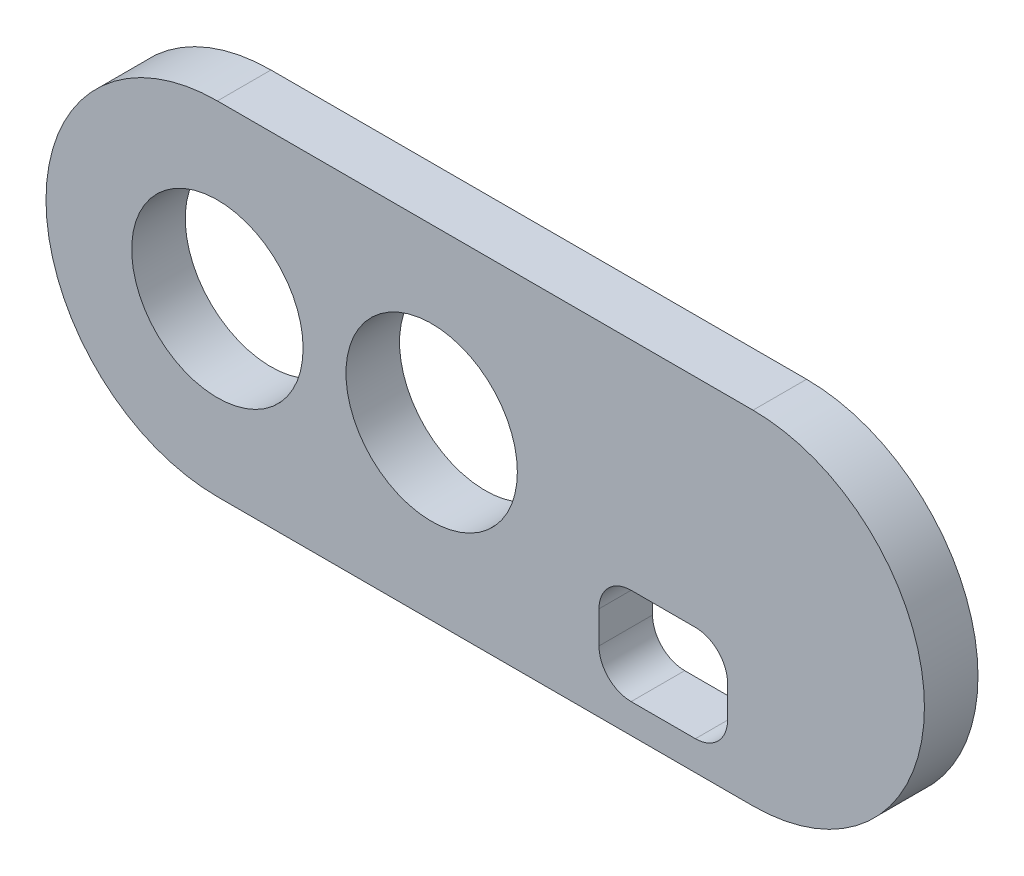
SolidWorks part; units mm, degrees
ref_plane "前视基准面" through (0, 0, 0) normal (0, 0, 1) x (1, 0, 0)
ref_plane "上视基准面" through (0, 0, 0) normal (0, 1, 0) x (1, 0, 0)
ref_plane "右视基准面" through (0, 0, 0) normal (1, 0, 0) x (0, 0, -1)
other "Configuration Table"
sketch "草图1" plane through (0, 0, 0) normal (0, 0, 1) x (1, 0, 0)
  line L0 (-21.649, 23.4111) -> (28.351, 23.4111) construction
  line L1 (-21.649, 39.4111) -> (19.1881, 39.4111)
  line L2 (-21.649, 7.4111) -> (19.1881, 7.4111)
  line L4 (19.1881, 39.4111) -> (28.351, 39.4111)
  line L5 (19.1881, 7.4111) -> (28.351, 7.4111)
  line L6 (19.9501, 38.4111) -> (28.351, 38.4111)
  line L7 (19.851, 8.4111) -> (28.351, 8.4111)
  line L8 (10.9456, 29.4807) -> (10.8465, 17.4902)
  line L10 (16.971, 19.1617) -> (22.971, 19.1617)
  line L11 (13.971, 16.1617) -> (13.971, 13.1617)
  line L12 (16.971, 10.1617) -> (22.971, 10.1617)
  line L13 (25.971, 16.1617) -> (25.971, 13.1617)
  arc A0 (-21.649, 39.4111) -> (-21.649, 7.4111) centre (-21.649, 23.4111) ccw
  arc A1 (28.351, 7.4111) -> (28.351, 39.4111) centre (28.351, 23.4111) ccw
  arc A2 (13.971, 16.1617) -> (16.971, 19.1617) centre (16.971, 16.1617) cw
  arc A3 (16.971, 10.1617) -> (13.971, 13.1617) centre (16.971, 13.1617) cw
  arc A4 (10.9456, 29.4807) -> (19.9501, 38.4111) centre (19.9501, 29.4063) cw
  arc A5 (28.351, 8.4111) -> (28.351, 38.4111) centre (28.351, 23.4111) ccw
  arc A6 (10.8465, 17.4902) -> (19.851, 8.4111) centre (19.851, 17.4158) ccw
  arc A9 (25.971, 16.1617) -> (22.971, 19.1617) centre (22.971, 16.1617) ccw
  arc A10 (22.971, 10.1617) -> (25.971, 13.1617) centre (22.971, 13.1617) ccw
  circle A11 centre (-21.649, 23.4111) radius 8
  circle A12 centre (-1.649, 23.4111) radius 8
  point P2 (-17.3867, 13.3324)
  dimension "D1" = 32
  dimension "D4" = 50
  dimension "D6" = 20
  dimension "D7" = 6
  dimension "D8" = 3
  dimension "D3" = 16
other "对齐组1"
extrude "凸台-拉伸1" add sketch "草图1" along normal blind 5
